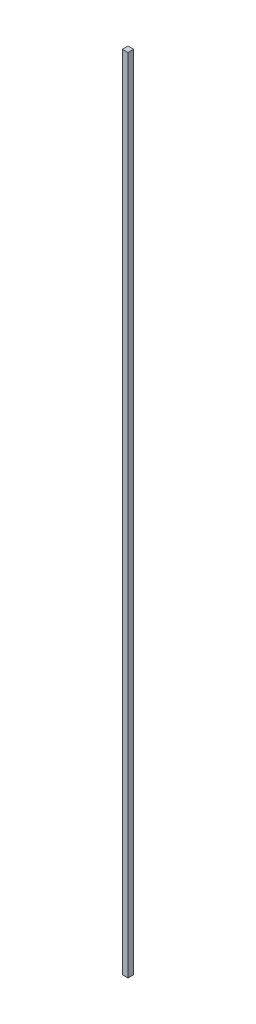
SolidWorks part; units mm, degrees
ref_plane "Front Plane" through (0, 0, 0) normal (0, 0, 1) x (1, 0, 0)
ref_plane "Top Plane" through (0, 0, 0) normal (0, 1, 0) x (1, 0, 0)
ref_plane "Right Plane" through (0, 0, 0) normal (1, 0, 0) x (0, 0, -1)
sketch "Sketch1" plane through (0, 0, 0) normal (0, 0, 1) x (1, 0, 0)
  line L1 (4, 570) -> (0, 570)
  line L2 (4, 570) -> (4, 0)
  line L3 (4, 0) -> (0, 0)
  line L4 (0, 570) -> (0, 0)
  circle A0 centre (40, 570) radius 40 construction
  point P4 (0, 492.4338)
  point P5 (4, 567.893)
  dimension "D1" = 4
extrude "Boss-Extrude1" add sketch "Sketch1" along normal blind 4
